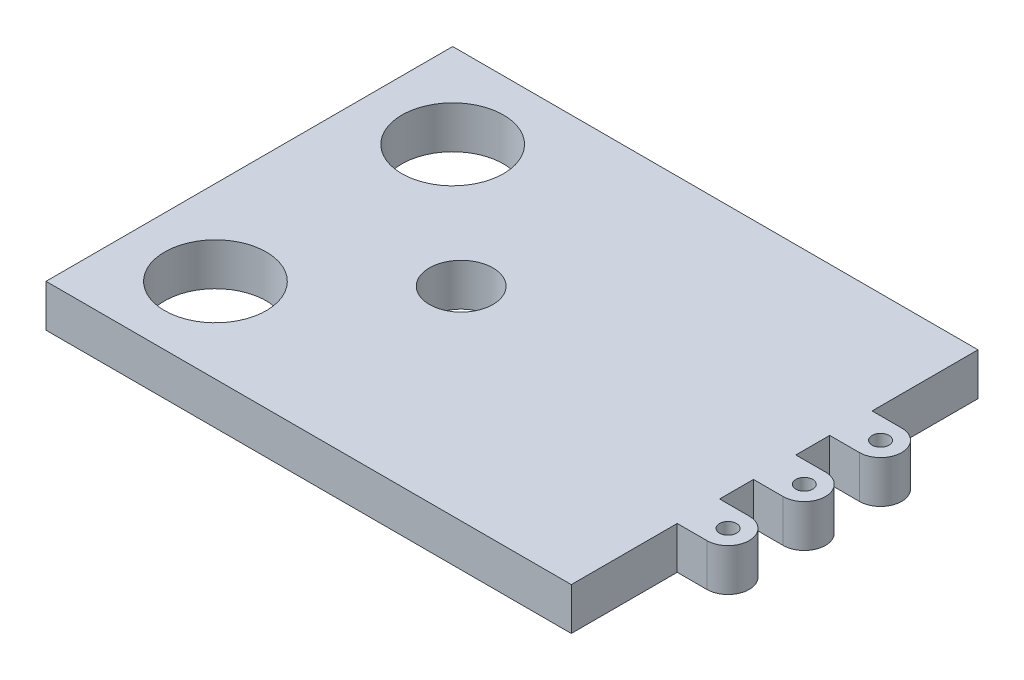
SolidWorks part; units mm, degrees
ref_plane "Front Plane" through (0, 0, 0) normal (0, 0, 1) x (1, 0, 0)
ref_plane "Top Plane" through (0, 0, 0) normal (0, 1, 0) x (1, 0, 0)
ref_plane "Right Plane" through (0, 0, 0) normal (1, 0, 0) x (0, 0, -1)
sketch "Sketch1" plane through (0, 0, 0) normal (0, 1, 0) x (1, 0, 0)
  line L1 (0, 0) -> (62, 0)
  line L2 (0, 0) -> (0, 48)
  line L3 (0, 48) -> (62, 48)
  line L5 (65.5, 35.5) -> (62, 35.5)
  line L7 (62, 48) -> (62, 35.5)
  line L10 (65.5, 30.5) -> (62, 30.5)
  line L11 (62, 30.5) -> (62, 26.5)
  line L12 (62, 26.5) -> (65.5, 26.5)
  line L13 (65.5, 21.5) -> (62, 21.5)
  line L14 (62, 30.5) -> (62, 26.5)
  line L15 (65.5, 17.5) -> (62, 17.5)
  line L16 (62, 21.5) -> (62, 17.5)
  line L17 (65.5, 12.5) -> (62, 12.5)
  line L18 (62, 12.5) -> (62, 0)
  circle A0 centre (10, 10) radius 6
  circle A1 centre (10, 38) radius 6
  circle A4 centre (25, 24) radius 3.75
  circle A8 centre (65.5, 15) radius 1
  circle A9 centre (65.5, 24) radius 1
  circle A10 centre (65.5, 33) radius 1
  arc A11 (65.5, 30.5) -> (65.5, 35.5) centre (65.5, 33) ccw
  arc A12 (65.5, 21.5) -> (65.5, 26.5) centre (65.5, 24) ccw
  arc A13 (65.5, 12.5) -> (65.5, 17.5) centre (65.5, 15) ccw
  point P1 (0, 0)
  point P15 (0, 24)
  dimension "D1" = 12
  dimension "D9" = 7.5
  dimension "D13" = 3.5
  dimension "D16" = 2
  dimension "D17" = 5
  dimension "D18" = 15
  dimension "D7" = 9
  dimension "D2" = 62
  dimension "D3" = 10
  dimension "D4" = 10
  dimension "D5" = 48
  dimension "D6" = 28
  dimension "D8" = 15
  dimension "D11" = 9
extrude "Boss-Extrude1" add sketch "Sketch1" along normal blind 5 contours L17 A13 L15 L16 L13 A12 L12 L11 L10 A11 L5 L7 L3 L2 L1 L18 A0 A1 A4 A8 A9 A10
